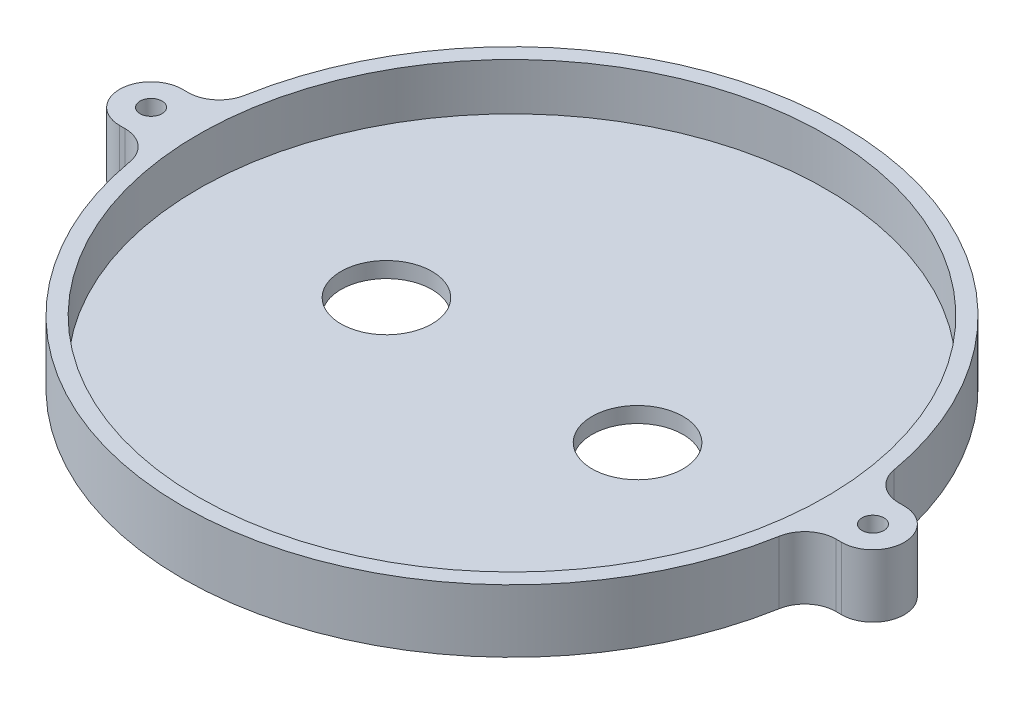
SolidWorks part; units mm, degrees
ref_plane "Front Plane" through (0, 0, 0) normal (0, 0, 1) x (1, 0, 0)
ref_plane "Top Plane" through (0, 0, 0) normal (0, 1, 0) x (1, 0, 0)
ref_plane "Right Plane" through (0, 0, 0) normal (1, 0, 0) x (0, 0, -1)
sketch "Sketch1" plane through (0, 0, 0) normal (0, 1, 0) x (1, 0, 0)
  circle A0 centre (0, 0) radius 50
  circle A1 centre (0, 0) radius 52.5
  dimension "D1" = 105
  dimension "D2" = 100
extrude "Boss-Extrude1" add sketch "Sketch1" along normal blind 7.5
sketch "Sketch2" plane through (0, 0, 0) normal (0, -1, 0) x (1, 0, 0)
  circle A0 centre (0, 0) radius 52.5
  dimension "D1" = 105
extrude "Boss-Extrude2" add sketch "Sketch2" along normal blind 2.5
sketch "Sketch3" plane through (0, -2.5, 0) normal (0, -1, 0) x (1, 0, 0)
  line L1 (-20, 15) -> (20, 15)
  line L2 (-20, 15) -> (-20, -15)
  line L3 (-20, -15) -> (20, -15)
  line L4 (20, 15) -> (20, -15)
  line L5 (-20, 15) -> (20, -15) construction
  line L6 (-20, -15) -> (20, 15) construction
  circle A0 centre (20, 0) radius 7.25
  circle A1 centre (-20, 0) radius 7.25
  point P0 (0, 0)
  dimension "D1" = 40
  dimension "D2" = 30
extrude "Cut-Extrude1" cut sketch "Sketch3" against normal through all contours A0 | A1
sketch "Sketch4" plane through (0, -2.5, 0) normal (0, -1, 0) x (1, 0, 0)
  line L0 (0, 0) -> (-52.5, 0)
  line L1 (-52.5, 0) -> (-62.5, 0)
  line L2 (-57.5, 5) -> (-52.2614, 5)
  line L5 (-52.2614, -5) -> (-57.5, -5)
  line L6 (-52.2614, -5) -> (-51.6586, 0)
  line L7 (-51.6586, 0) -> (-52.2614, 5)
  circle A0 centre (0, 0) radius 52.5 construction
  arc A1 (-57.5, 5) -> (-57.5, -5) centre (-57.5, 0) ccw
  circle A2 centre (-57.5, 0) radius 1.75
  dimension "D2" = 3.5
  dimension "D1" = 10
extrude "Boss-Extrude3" add sketch "Sketch4" against normal blind 10 contours A2 | A1 L5 L6 L7 L2
mirror "Mirror1" about plane through (0, 0, 0) normal (1, 0, 0) of "Boss-Extrude3"
fillet "Fillet1" radius 5 4 edges at (52.2614, 2.5, 5) (52.2614, 2.5, -5) (-52.2614, 2.5, 5) (-52.2614, 2.5, -5)
